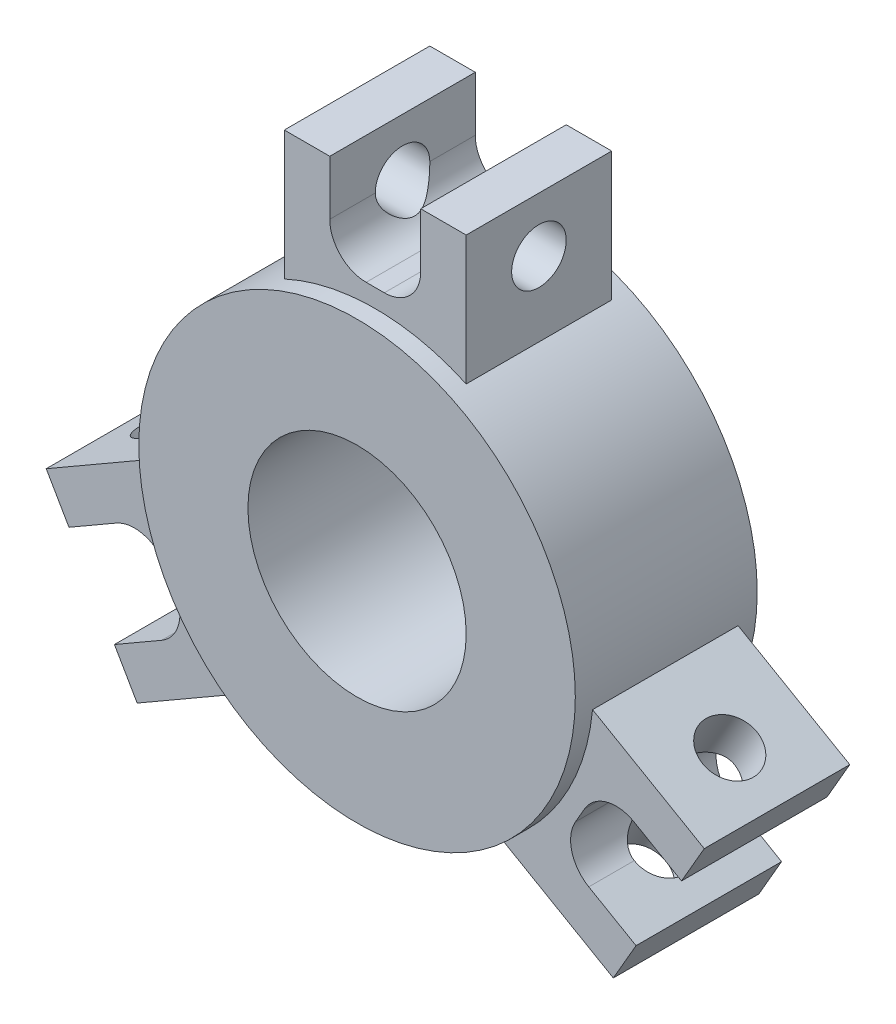
SolidWorks part; units mm, degrees
ref_plane "Alzado" through (0, 0, 0) normal (0, 0, 1) x (1, 0, 0)
ref_plane "Planta" through (0, 0, 0) normal (0, 1, 0) x (1, 0, 0)
ref_plane "Vista lateral" through (0, 0, 0) normal (1, 0, 0) x (0, 0, -1)
sketch "Croquis1" plane through (0, 0, 0) normal (0, 0, 1) x (1, 0, 0)
  line L0 (0, 7.0475) -> (0, 0) construction
  line L1 (0, 0) -> (-7.791, -4.4982) construction
  line L2 (-0.084, -0.0485) -> (7.2425, -4.2784) construction
  circle A0 centre (0, 0) radius 3
  circle A1 centre (0, 0) radius 6
  dimension "D1" = 6
  dimension "D3" = 120
  dimension "D4" = 120
  dimension "D2" = 3
extrude "Saliente-Extruir1" add sketch "Croquis1" along normal mid plane 5
sketch "Croquis3" plane through (0, 0, 0) normal (1, 0, 0) x (0, 0, -1)
  line L1 (-2, 9) -> (2, 9)
  line L2 (-2, 9) -> (-2, 5)
  line L3 (-2, 5) -> (2, 5)
  line L4 (2, 9) -> (2, 5)
  circle A0 centre (0, 7.5) radius 0.75
  point P4 (0, 5)
  dimension "D3" = 1.5
  dimension "D1" = 4
  dimension "D2" = 5
  dimension "D4" = 2.5
extrude "Saliente-Extruir2" add sketch "Croquis3" along normal mid plane 5
sketch "Croquis4" plane through (0, 0, 2) normal (0, 0, 1) x (1, 0, 0)
  line L0 (2.5, 9) -> (-2.5, 9) construction
  line L1 (-1.25, 9) -> (1.25, 9)
  line L2 (-1.25, 9) -> (-1.25, 7.5)
  line L3 (-0.25, 6.5) -> (0.25, 6.5)
  line L4 (1.25, 9) -> (1.25, 7.5)
  arc A0 (0.25, 6.5) -> (1.25, 7.5) centre (0.25, 7.5) ccw
  arc A1 (-1.25, 7.5) -> (-0.25, 6.5) centre (-0.25, 7.5) ccw
  point P6 (0, 6.5)
  dimension "D3" = 1
  dimension "D1" = 6.5
  dimension "D2" = 2.5
extrude "Cortar-Extruir1" cut sketch "Croquis4" against normal blind 5
sketch "Croquis5" plane through (0, 0, 0) normal (1, 0, 0) x (0, 0, -1)
  line L0 (0, 0) -> (50000, 0) construction
pattern_circular "MatrizC1" count 3 over 360 about axis through (0, 0, 0) along (0, 0, 1) of "Cortar-Extruir1", "Saliente-Extruir2"
